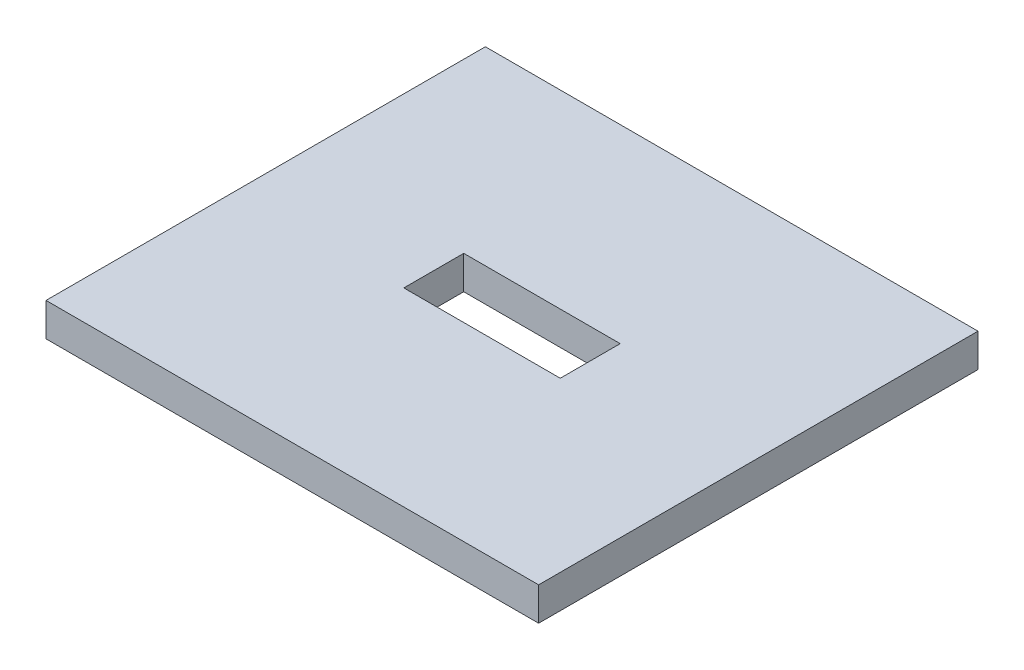
SolidWorks part; units mm, degrees
ref_plane "Ön Düzlem" through (0, 0, 0) normal (0, 0, 1) x (1, 0, 0)
ref_plane "Üst Düzlem" through (0, 0, 0) normal (0, 1, 0) x (1, 0, 0)
ref_plane "Sağ Düzlem" through (0, 0, 0) normal (1, 0, 0) x (0, 0, -1)
sketch "Çizim1" plane through (0, 0, 0) normal (0, 1, 0) x (1, 0, 0)
  line L1 (0, 0) -> (74, 0)
  line L2 (0, 0) -> (0, 66)
  line L3 (0, 66) -> (74, 66)
  line L4 (74, 0) -> (74, 66)
  line L5 (25.25, 37.5) -> (48.75, 37.5)
  line L6 (25.25, 37.5) -> (25.25, 28.5)
  line L7 (25.25, 28.5) -> (48.75, 28.5)
  line L8 (48.75, 37.5) -> (48.75, 28.5)
  dimension "D1" = 74
  dimension "D2" = 66
  dimension "D3" = 23.5
  dimension "D4" = 9
  dimension "D5" = 28.5
  dimension "D6" = 25.25
extrude "Yükseklik-Ekstrüzyon1" add sketch "Çizim1" along normal blind 5
